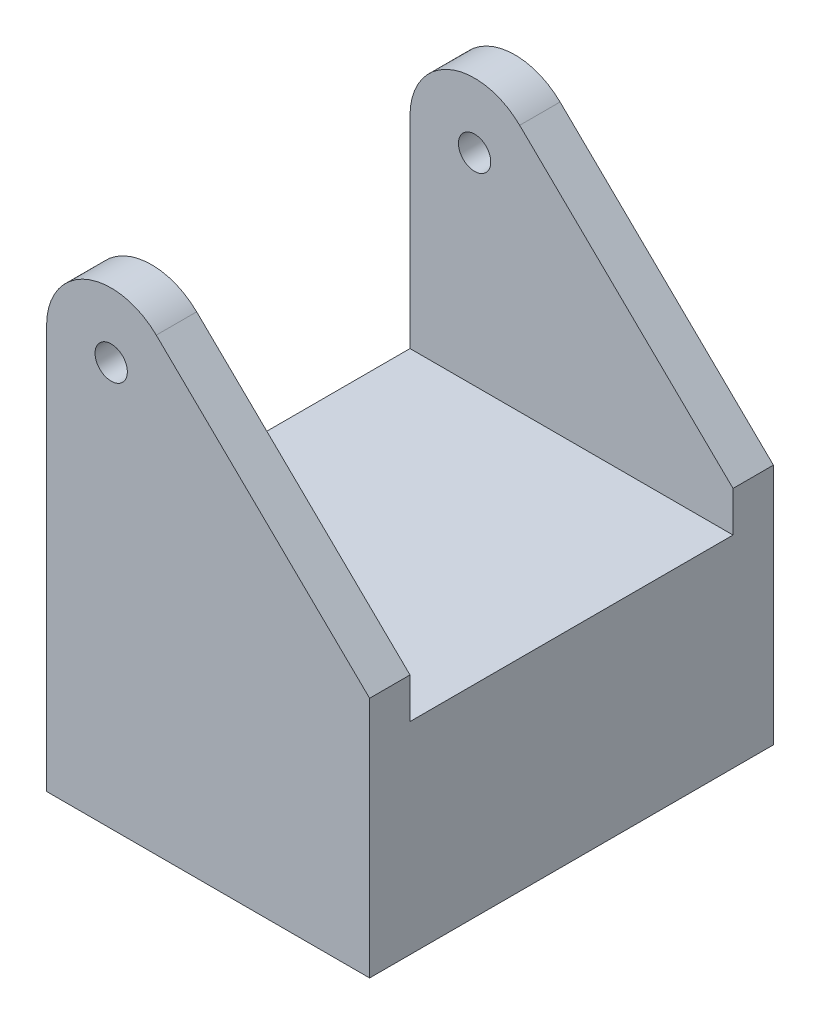
SolidWorks part; units mm, degrees
ref_plane "Alzado" through (0, 0, 0) normal (0, 0, 1) x (1, 0, 0)
ref_plane "Planta" through (0, 0, 0) normal (0, 1, 0) x (1, 0, 0)
ref_plane "Vista lateral" through (0, 0, 0) normal (1, 0, 0) x (0, 0, -1)
sketch "Croquis3" plane through (0, 0, 0) normal (0, 0, 1) x (1, 0, 0)
  line L0 (0, 250) -> (0, 262.4043) construction
  line L1 (0, 0) -> (200, 0)
  line L2 (0, 0) -> (0, 150)
  line L4 (200, 0) -> (200, 150)
  line L6 (0, 150) -> (0, 250)
  line L7 (200, 150) -> (67.9091, 278.6545)
  line L8 (67.9091, 278.6545) -> (200, 150)
  arc A0 (67.9091, 278.6545) -> (0, 250) centre (40, 250) ccw
  dimension "D3" = 80
  dimension "D1" = 150
  dimension "D2" = 200
  dimension "D4" = 112.4043
extrude "Saliente-Extruir3" add sketch "Croquis3" along normal blind 250 contours L7 A0 L6 L2 L1 L4
sketch "Croquis6" plane through (0, 0, 0) normal (0, 0, -1) x (-1, 0, 0)
  circle A0 centre (-40, 250) radius 10
  dimension "D1" = 20
extrude "Cortar-Extruir1" cut sketch "Croquis6" against normal blind 264
sketch "Croquis7" plane through (0, 0, 0) normal (-1, 0, 0) x (0, 0, 1)
  line L0 (250, 290) -> (0, 290) construction
  line L1 (25, 290) -> (225, 290)
  line L2 (25, 290) -> (25, 125)
  line L3 (25, 125) -> (225, 125)
  line L4 (225, 290) -> (225, 125)
  line L5 (250, 250) -> (250, 290) construction
  line L6 (0, 290) -> (0, 250) construction
  point P8 (0, 270)
  dimension "D1" = 25
  dimension "D2" = 25
  dimension "D3" = 165
extrude "Cortar-Extruir3" cut sketch "Croquis7" against normal blind 264
